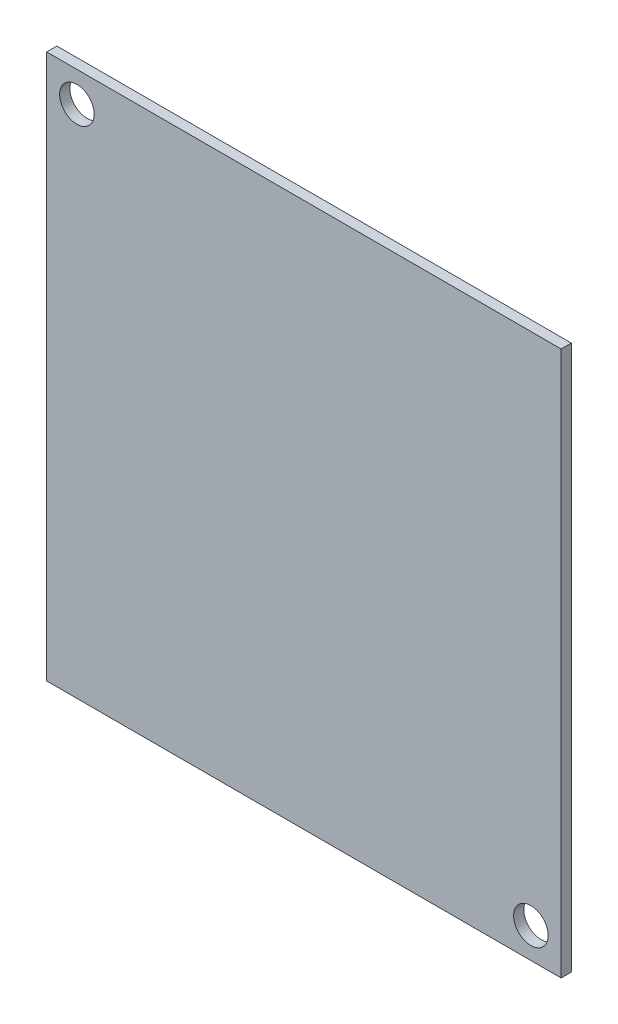
SolidWorks part; units mm, degrees
material "Thornel VCB-20 Carbon Cloth"
ref_plane "Спереди" through (0, 0, 0) normal (0, 0, 1) x (1, 0, 0)
ref_plane "Сверху" through (0, 0, 0) normal (0, 1, 0) x (1, 0, 0)
ref_plane "Справа" through (0, 0, 0) normal (1, 0, 0) x (0, 0, -1)
sketch "Sketch1" plane through (0, 0, 0) normal (0, 0, 1) x (1, 0, 0)
  line L1 (0, 0) -> (75.565, 0)
  line L2 (0, 0) -> (0, 80.01)
  line L3 (0, 80.01) -> (75.565, 80.01)
  line L4 (75.565, 0) -> (75.565, 80.01)
  circle A0 centre (4.445, 75.565) radius 2.54
  circle A1 centre (71.12, 4.445) radius 2.54
  dimension "D3" = 5.08
  dimension "D4" = 4.445
  dimension "D5" = 4.445
  dimension "D6" = 4.445
  dimension "D7" = 4.445
  dimension "D1" = 75.565
  dimension "D2" = 80.01
extrude "Boss-Extrude1" add sketch "Sketch1" along normal blind 1.5
